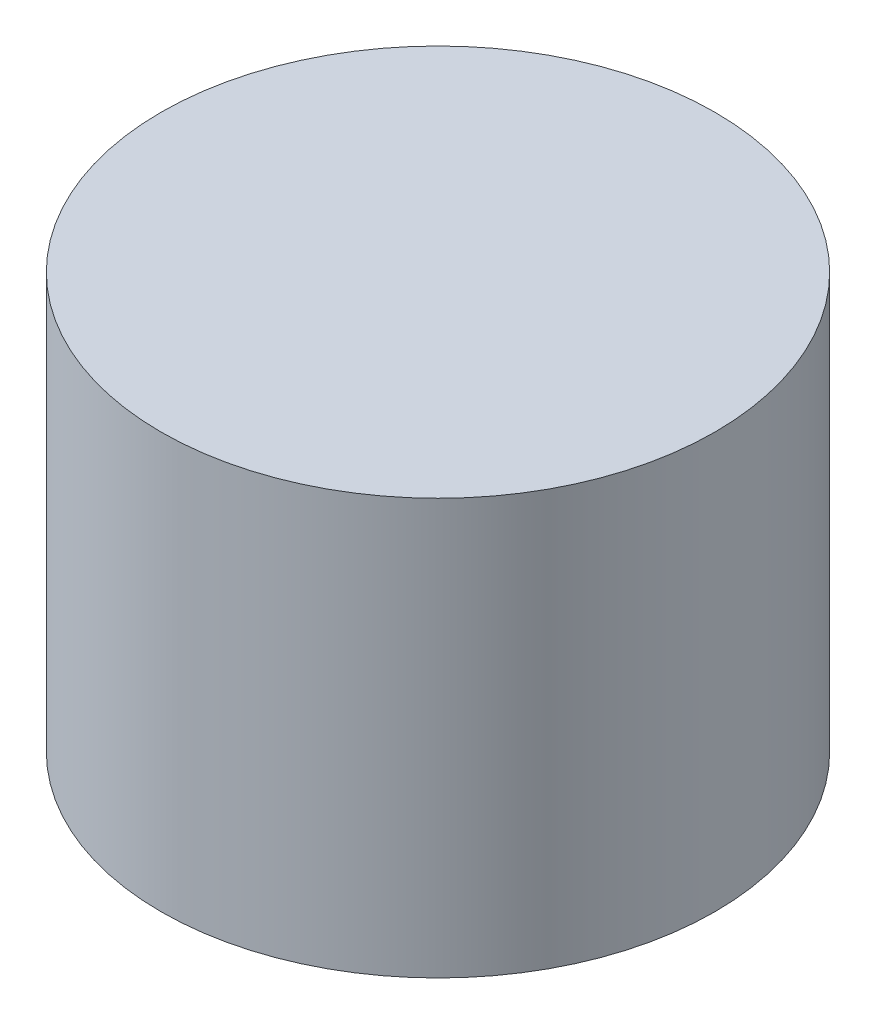
SolidWorks part; units mm, degrees
material "Balsa"
ref_plane "Front" through (0, 0, 0) normal (0, 0, 1) x (1, 0, 0)
ref_plane "Top" through (0, 0, 0) normal (0, 1, 0) x (1, 0, 0)
ref_plane "Right" through (0, 0, 0) normal (1, 0, 0) x (0, 0, -1)
sketch "Esboço1" plane through (0, 0, 0) normal (0, 1, 0) x (1, 0, 0)
  circle A0 centre (0, 0) radius 4
extrude "Ressalto-extrusão1" add sketch "Esboço1" along normal blind 6
